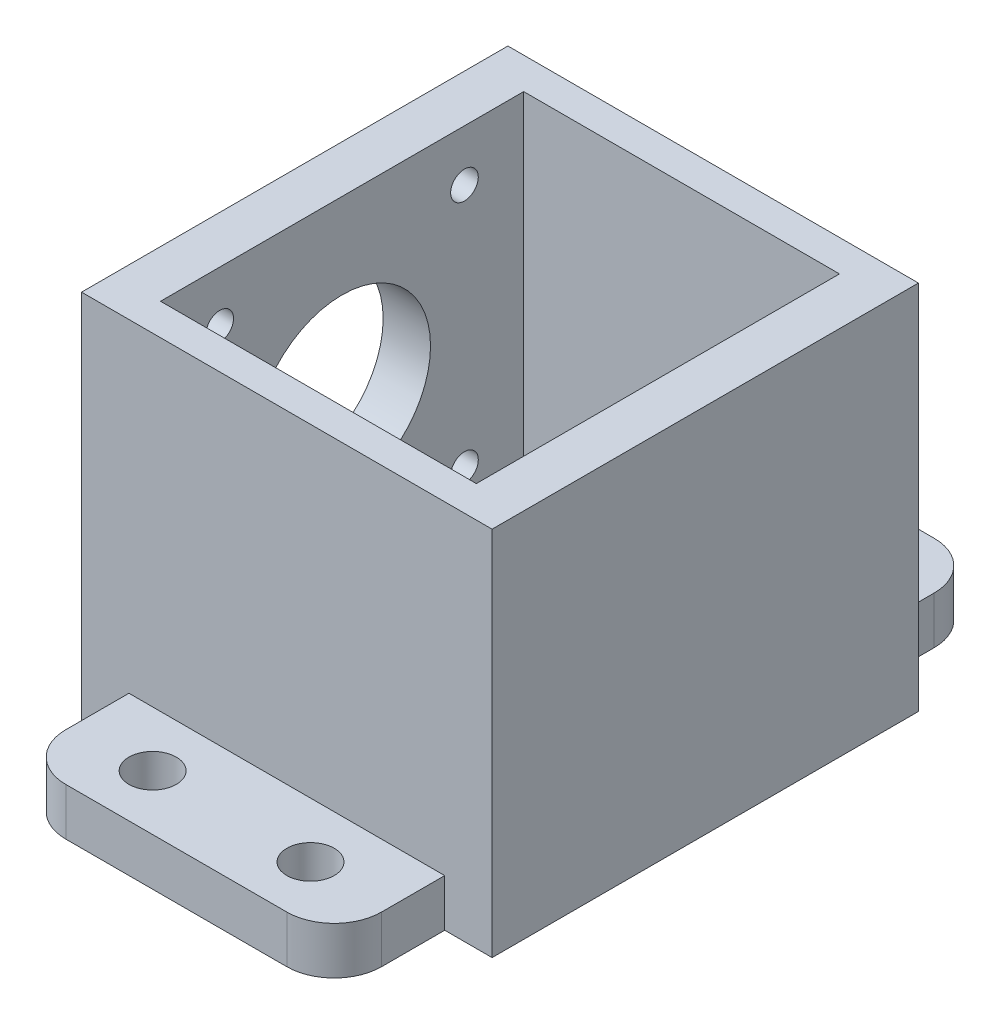
SolidWorks part; units mm, degrees
material "聚脂树脂"
ref_plane "前视基准面" through (0, 0, 0) normal (0, 0, 1) x (1, 0, 0)
ref_plane "上视基准面" through (0, 0, 0) normal (0, 1, 0) x (1, 0, 0)
ref_plane "右视基准面" through (0, 0, 0) normal (1, 0, 0) x (0, 0, -1)
other "Configuration Table"
sketch "草图1" plane through (0, 0, 0) normal (0, 1, 0) x (1, 0, 0)
  line L0 (-109.5286, 0) -> (219.4031, 0) construction
  line L1 (-26, -27) -> (26, -27)
  line L2 (-26, -27) -> (-26, 27)
  line L3 (-26, 27) -> (26, 27)
  line L4 (26, -27) -> (26, 27)
  line L5 (0, 86.7184) -> (0, -86.6898) construction
  line L6 (57, 86.7184) -> (57, -86.6898) construction
  dimension "D1" = 54
  dimension "D3" = 57
  dimension "D4" = 52
extrude "凸台-拉伸1" add sketch "草图1" along normal blind 47
sketch "草图2" plane through (0, 0, 0) normal (0, 1, 0) x (1, 0, 0)
  line L6 (26, 27) -> (-26, 27) construction
  line L7 (-20, 23) -> (20, 23)
  line L12 (-20, 23) -> (-20, -23)
  line L13 (-20, -23) -> (20, -23)
  line L14 (20, 23) -> (20, -23)
  line L15 (-12.1187, 0) -> (74.6821, 0) construction
  line L16 (-26, 27) -> (-26, -27) construction
  line L17 (26, -27) -> (26, 27) construction
  dimension "D1" = 4
  dimension "D2" = 6
  dimension "D3" = 6
extrude "切除-拉伸1" cut sketch "草图2" against normal blind 43 from surface at 47 starting at face at (0, 47, 0)
sketch "草图4" plane through (0, 0, 0) normal (1, 0, 0) x (0, 0, -1)
  line L0 (-36.4632, 25) -> (43.9373, 25) construction
  line L1 (0, 56.727) -> (0, -8.7062) construction
  circle A0 centre (0, 25) radius 11.2
  circle A1 centre (-15.5, 40.5) radius 1.75
  circle A2 centre (15.5, 40.5) radius 1.75
  circle A3 centre (15.5, 9.5) radius 1.75
  circle A4 centre (-15.5, 9.5) radius 1.75
  dimension "D2" = 22.4
  dimension "D5" = 3.5
  dimension "D1" = 25
  dimension "D3" = 31
  dimension "D4" = 31
extrude "切除-拉伸3" cut sketch "草图4" against normal up to surface (6 mm away) from surface at -20 up to face at (-26, 23.5, 0) starting at face at (-20, 25.5, 0)
sketch "草图5" plane through (0, 0, 0) normal (0, 1, 0) x (1, 0, 0)
  line L0 (-80.7916, 0) -> (182.8619, 0) construction
  line L1 (-20, 27) -> (20, 27)
  line L2 (-20, 27) -> (-20, 41)
  line L3 (-20, 41) -> (20, 41)
  line L4 (20, 27) -> (20, 41)
  line L5 (-20, -27) -> (20, -27)
  line L6 (-20, -27) -> (-20, -41)
  line L7 (-20, -41) -> (20, -41)
  line L8 (20, -27) -> (20, -41)
  line L9 (0, 83.4272) -> (0, -59.3244) construction
  line L10 (26, 27) -> (-26, 27) construction
  circle A0 centre (-10, 34) radius 3
  circle A1 centre (10, 34) radius 3
  circle A2 centre (10, -34) radius 3
  circle A3 centre (-10, -34) radius 3
  point P19 (0, 0)
  point P24 (0, 0)
  point P25 (0, 0)
  dimension "D4" = 6
  dimension "D1" = 40
  dimension "D2" = 14
  dimension "D5" = 20
  dimension "D6" = 7
extrude "凸台-拉伸2" add sketch "草图5" along normal blind 6
fillet "圆角1" radius 6 4 edges at (20, 3, -41) (-20, 3, -41) (20, 3, 41) (-20, 3, 41)
